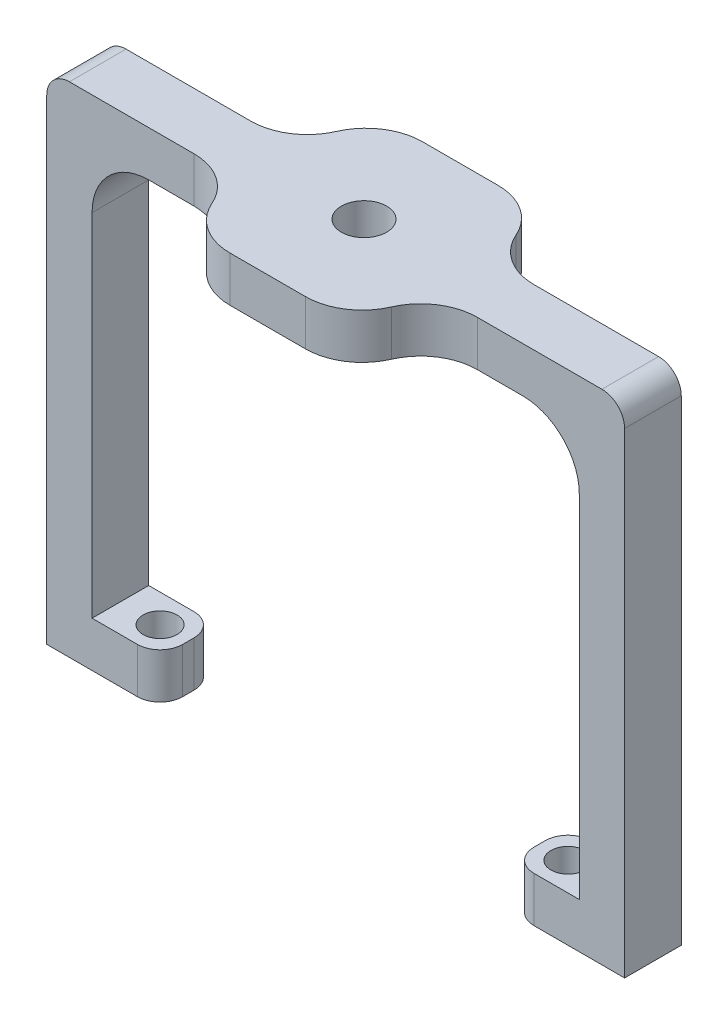
SolidWorks part; units mm, degrees
other "标注1"
sketch "草图6" plane through (10, 54, 5) normal (0.354, 0.6312, 0.6902) x (0.9298, -0.1576, -0.3327)
ref_plane "前视基准面" through (0, 0, 0) normal (0, 0, 1) x (1, 0, 0)
ref_plane "上视基准面" through (0, 0, 0) normal (0, 1, 0) x (1, 0, 0)
ref_plane "右视基准面" through (0, 0, 0) normal (1, 0, 0) x (0, 0, -1)
other "Configuration Table"
sketch "草图1" plane through (0, 0, 0) normal (0, 1, 0) x (1, 0, 0)
  line L1 (0, 0) -> (10, 0)
  line L2 (0, 0) -> (0, -5)
  line L3 (0, -5) -> (10, -5)
  line L4 (10, 0) -> (10, -5)
  dimension "D1" = 5
  dimension "D2" = 10
extrude "凸台-拉伸1" add sketch "草图1" along normal blind 4
sketch "草图3" plane through (0, 4, 0) normal (0, 1, 0) x (1, 0, 0)
  line L0 (10, -2.5) -> (0, -2.5) construction
  line L1 (10, -5) -> (10, 0) construction
  line L2 (0, 0) -> (0, -5) construction
  circle A0 centre (7.5, -2.5) radius 1.5
  point P8 (0, 0)
  dimension "D1" = 3
  dimension "D2" = 2.5
extrude "切除-拉伸1" cut sketch "草图3" against normal blind 4
sketch "草图4" plane through (0, 4, 0) normal (0, 1, 0) x (1, 0, 0)
  line L0 (0, -5) -> (10, -5) construction
  line L1 (0, 0) -> (4, 0)
  line L2 (0, 0) -> (0, -5)
  line L3 (0, -5) -> (4, -5)
  line L4 (4, 0) -> (4, -5)
  dimension "D1" = 4
extrude "凸台-拉伸2" add sketch "草图4" along normal blind 40
sketch "草图5" plane through (4, 0, 0) normal (1, 0, 0) x (0, 0, -1)
  line L0 (0, 44) -> (0, 4) construction
  line L1 (-5, 44) -> (0, 44)
  line L2 (-5, 44) -> (-5, 40)
  line L3 (-5, 40) -> (0, 40)
  line L4 (0, 44) -> (0, 40)
  dimension "D1" = 4
extrude "凸台-拉伸3" add sketch "草图5" along normal blind 47
sketch "草图7" plane through (0, 40, 0) normal (0, -1, 0) x (-1, 0, 0)
  line L0 (-51, 0) -> (-4, 0) construction
  line L1 (-51, -5) -> (-47, -5)
  line L2 (-51, -5) -> (-51, 0)
  line L3 (-51, 0) -> (-47, 0)
  line L4 (-47, -5) -> (-47, 0)
  dimension "D1" = 4
extrude "凸台-拉伸4" add sketch "草图7" along normal up to surface (40 mm away) up to face at (7.5, 0, 4)
sketch "草图8" plane through (47, 0, 0) normal (-1, 0, 0) x (0, 0, 1)
  line L0 (5, 44) -> (5, 0) construction
  line L1 (0, 0) -> (5, 0)
  line L2 (0, 0) -> (0, 4)
  line L3 (0, 4) -> (5, 4)
  line L4 (5, 0) -> (5, 4)
  dimension "D1" = 4
extrude "凸台-拉伸5" add sketch "草图8" along normal blind 6
sketch "草图10" plane through (0, 0, 0) normal (0, -1, 0) x (-1, 0, 0)
  line L0 (-41, -2.5) -> (-44.7473, -2.5) construction
  line L1 (-41, 0) -> (-41, -5) construction
  circle A0 centre (-43.5, -2.5) radius 1.5
  dimension "D2" = 3
  dimension "D1" = 2.5
extrude "切除-拉伸2" cut sketch "草图10" against normal blind 6
sketch "草图11" plane through (0, 0, 0) normal (0, 0, -1) x (-1, 0, 0)
  line L0 (-25.5, 44) -> (-25.5, 40) construction
  line L1 (-51, 44) -> (0, 44) construction
  line L2 (-47, 40) -> (-4, 40) construction
  line L4 (-33, 44) -> (-18, 44)
  line L5 (-33, 44) -> (-33, 40)
  line L6 (-33, 40) -> (-18, 40)
  line L7 (-18, 44) -> (-18, 40)
  dimension "D1" = 15
  dimension "D2" = 7.5
extrude "凸台-拉伸6" add sketch "草图11" along normal blind 6 and the other way blind 11
fillet "圆角1" radius 5 4 edges at (33, 42, 5) (33, 42, 0) (18, 42, 5) (18, 42, 0)
sketch "草图12" plane through (0, 44, 0) normal (0, 1, 0) x (1, 0, 0)
  line L0 (25.5, 6) -> (25.5, -11) construction
  line L1 (18, 6) -> (33, 6) construction
  line L2 (18, -11) -> (33, -11) construction
  circle A0 centre (25.5, -2.5) radius 2
  dimension "D1" = 4
extrude "切除-拉伸3" cut sketch "草图12" against normal blind 6
fillet "圆角2" radius 5 4 edges at (18, 42, -6) (33, 42, -6) (33, 42, 11) (18, 42, 11)
fillet "圆角3" radius 5 2 edges at (47, 40, 2.5) (4, 40, 2.5)
fillet "圆角4" radius 2 2 edges at (10, 2, 0) (10, 2, 5)
fillet "圆角5" radius 2 4 edges at (0, 44, 2.5) (51, 44, 2.5) (41, 2, 0) (41, 2, 5)
